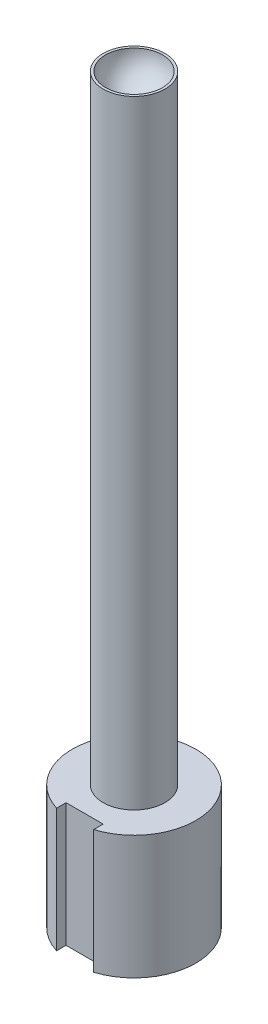
SolidWorks part; units mm, degrees
material "Alumina"
ref_plane "Front Plane" through (0, 0, 0) normal (0, 0, 1) x (1, 0, 0)
ref_plane "Top Plane" through (0, 0, 0) normal (0, 1, 0) x (1, 0, 0)
ref_plane "Right Plane" through (0, 0, 0) normal (1, 0, 0) x (0, 0, -1)
sketch "Sketch1" plane through (0, 0, 0) normal (0, 1, 0) x (1, 0, 0)
  line L0 (0, -5.5) -> (0, 5.5) construction
  line L5 (-5.5, 0) -> (5.5, 0) construction
  circle A1 centre (0, 0) radius 5
  dimension "D1" = 10
extrude "Boss-Extrude1" add sketch "Sketch1" along normal blind 10
sketch "Sketch2" plane through (0, 10, 0) normal (0, 1, 0) x (1, 0, 0)
  circle A0 centre (0, 0) radius 2.5
  circle A1 centre (0, 0) radius 5 construction
  dimension "D1" = 5
extrude "Boss-Extrude2" add sketch "Sketch2" along normal blind 50
sketch "Sketch7" plane through (0, 0, 0) normal (0, 0, 1) x (1, 0, 0)
  line L0 (2.5, 60) -> (-2.5, 60) construction
  line L1 (2.3, 60) -> (0, 60)
  line L2 (0, 60) -> (0, 57.7)
  arc A0 (2.3, 60) -> (0, 57.7) centre (0, 60) cw
  point P2 (1.15, 60)
  point P7 (0, 0)
  dimension "D2" = 0.2
revolve "Cut-Revolve1" cut sketch "Sketch7" angle 360 about L2
sketch "Sketch8" plane through (0, 0, 0) normal (1, 0, 0) x (0, 0, -1)
  line L0 (5, 10) -> (-5, 10) construction
  circle A0 centre (0, 5) radius 1.8
  dimension "D1" = 3.6
  dimension "D2" = 5
sketch "Sketch9" plane through (0, 0, 0) normal (0, -1, 0) x (1, 0, 0)
  line L1 (-1.5, 5.4209) -> (1.5, 5.4209)
  line L2 (-1.5, 5.4209) -> (-1.5, 4)
  line L3 (-1.5, 4) -> (1.5, 4)
  line L4 (1.5, 5.4209) -> (1.5, 4)
  circle A0 centre (0, 0) radius 5 construction
  point P4 (0, 4)
  dimension "D1" = 3
  dimension "D2" = 4
extrude "Cut-Extrude2" cut sketch "Sketch9" against normal blind 10
hole_wizard "Tap Drill for M3x0.5 Tap1" [suppressed] positions "Sketch10" profile "Sketch12" hole size "M3x0.5" standard "ANSI Metric"
sketch "Sketch10" plane through (0, 0, 0) normal (0, -1, 0) x (-1, 0, 0)
  point P0 (0, 0)
sketch "Sketch12" plane through (0, 0, 0) normal (1, 0, 0) x (0, 0, -1)
  line L0 (0, 0) -> (0, 5.7511)
  line L1 (0, 5.7511) -> (1.25, 5)
  line L2 (1.25, 5) -> (1.25, 0.025)
  line L3 (1.25, 0.025) -> (1.275, 0)
  line L5 (1.275, 0) -> (0, 0)
  line L6 (-1.25, 0.025) -> (-1.275, 0) construction
  line L10 (0, 5.7511) -> (-1.25, 5) construction
  line L11 (0, -6.35) -> (0, 107.95) construction
  dimension "Hole Dia." = 2.5
  dimension "Hole Depth" = 5
  dimension "Near C'Sink Dia." = 2.55
  dimension "Near C'Sink Angle" = 90
  dimension "Drill Angle" = 118
sketch "Sketch13" plane through (0, 0, 0) normal (0, -1, 0) x (1, 0, 0)
  point P0 (0, 0)
hole_wizard "Tap Drill for M3x0.5 Tap2" positions "Sketch13" profile "Sketch14" hole size "M3x0.5" standard "ANSI Metric"
sketch "Sketch14" plane through (0, 0, 0) normal (1, 0, 0) x (0, 0, -1)
  line L0 (0, 0) -> (0, 5.7511)
  line L1 (0, 5.7511) -> (1.25, 5)
  line L2 (1.25, 5) -> (1.25, 0.025)
  line L3 (1.25, 0.025) -> (1.275, 0)
  line L5 (1.275, 0) -> (0, 0)
  line L6 (-1.25, 0.025) -> (-1.275, 0) construction
  line L10 (0, 5.7511) -> (-1.25, 5) construction
  line L11 (0, -6.35) -> (0, 107.95) construction
  dimension "Hole Dia." = 2.5
  dimension "Hole Depth" = 5
  dimension "Near C'Sink Dia." = 2.55
  dimension "Near C'Sink Angle" = 90
  dimension "Drill Angle" = 118
ref_plane "Plane2" [suppressed] through (0, 30, 0) normal (0, 1, 0) x (1, 0, 0)
sketch "Sketch6" [suppressed] plane through (0, 30, 0) normal (0, 1, 0) x (1, 0, 0)
  circle A0 centre (5, 5) radius 2
  circle A1 centre (5, 7) radius 0.8
  circle A2 centre (6.5637, 6.247) radius 0.8
  circle A3 centre (5, 5) radius 2
  circle A4 centre (6.9499, 4.555) radius 0.8
  circle A5 centre (5, 5) radius 2
  circle A6 centre (5.8678, 3.1981) radius 0.8
  circle A7 centre (5, 5) radius 2
  circle A8 centre (4.1322, 3.1981) radius 0.8
  circle A9 centre (5, 5) radius 2
  circle A10 centre (3.0501, 4.555) radius 0.8
  circle A11 centre (5, 5) radius 2
  circle A12 centre (3.4363, 6.247) radius 0.8
  circle A13 centre (5, 5) radius 2
  point P25 (5, 5)
  dimension "D1" = 4
  dimension "D2" = 1.6
  dimension "D3" = 7
extrude "Boss-Extrude3" [suppressed] add sketch "Sketch6" along normal up to surface (15 mm away) contours A12 A0 A10 A8 A6 A4 A2 A1
